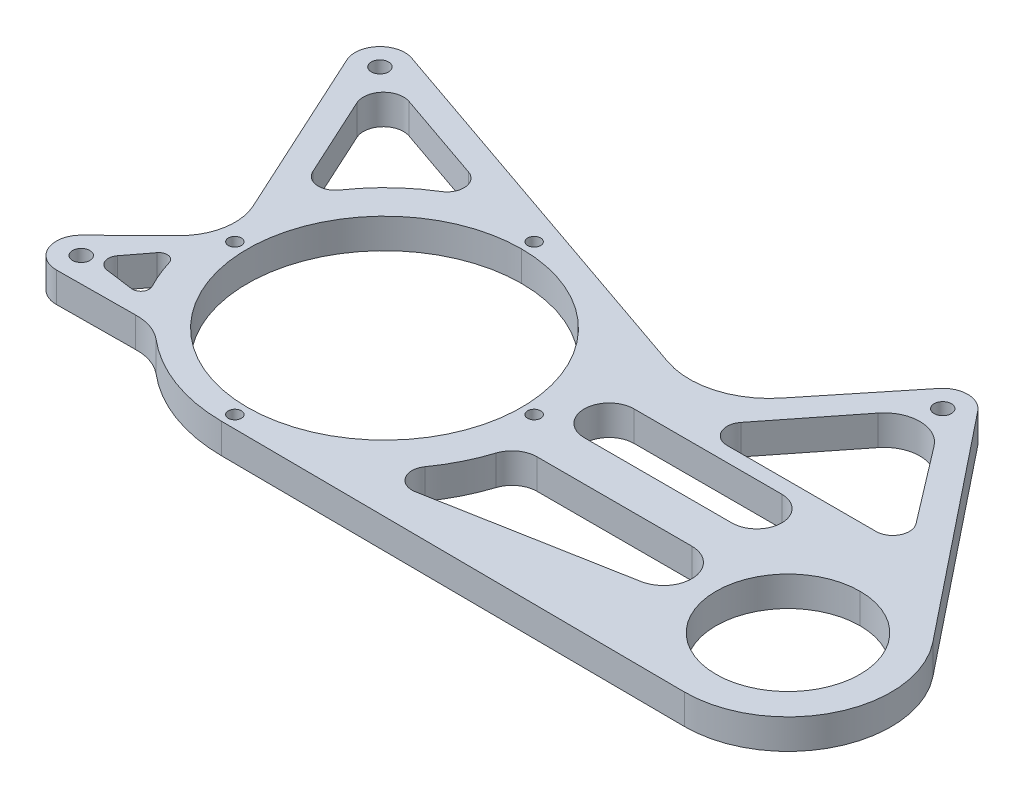
SolidWorks part; units mm, degrees
material "7075-T6 (SN)"
ref_plane "X-Y Datum" through (0, 0, 0) normal (0, 0, 1) x (1, 0, 0)
ref_plane "X-Z Datum" through (0, 0, 0) normal (0, 1, 0) x (1, 0, 0)
ref_plane "Y-Z Datum" through (0, 0, 0) normal (1, 0, 0) x (0, 0, -1)
sketch "Sketch1" plane through (0, 0, 0) normal (0, 1, 0) x (1, 0, 0)
  line L1 (0, 0) -> (54.61, -127) construction
  line L2 (-123.19, -103.3015) -> (54.61, -127) construction
  line L3 (-228.6, -146.8882) -> (-228.6, 0) construction
  line L4 (-116.84, 0) -> (0, 0) construction
  line L5 (-228.6, 0) -> (-116.84, 0) construction
  line L10 (-228.6, 0) -> (-123.19, -103.3015) construction
  line L11 (-123.19, -103.3015) -> (10.0337, -23.3342) construction
  line L15 (-207.3527, -8.7739) -> (-58.0195, -60.2909)
  line L16 (-123.5924, -165.2127) -> (54.3541, -166.3692)
  line L17 (17.4773, -17.3912) -> (85.3768, -102.4358)
  line L18 (2.625, -17.3478) -> (-24.2401, -50.596)
  line L21 (-219.114, -21.7551) -> (-188.6781, -87.992)
  line L23 (-228.6, -146.8882) -> (-123.19, -103.3015) construction
  line L26 (-205.0543, -146.7071) -> (-175.1551, -146.4772)
  line L27 (-211.8024, -130.3874) -> (-193.0929, -112.0085)
  circle A0 centre (-210.459, -17.7782) radius 9.525 construction
  circle A2 centre (10.0337, -23.3342) radius 9.525 construction
  circle A3 centre (-210.459, -17.7782) radius 3.3 construction
  circle A4 centre (-205.1275, -137.1824) radius 3.3 construction
  circle A5 centre (-123.19, -103.3015) radius 52.3875
  circle A6 centre (54.61, -127) radius 27.5
  circle A7 centre (0, 0) radius 12.7 construction
  circle A8 centre (-228.6, -146.8882) radius 12.7 construction
  circle A9 centre (-228.6, 0) radius 12.7 construction
  circle A10 centre (10.0337, -23.3342) radius 3.3 construction
  circle A11 centre (-123.19, -160.4515) radius 2.5 construction
  circle A14 centre (-123.19, -103.3015) radius 61.9125 construction
  circle A15 centre (-123.19, -103.3015) radius 57.15 construction
  circle A17 centre (-205.1275, -137.1824) radius 9.525 construction
  circle A18 centre (54.61, -127) radius 39.37 construction
  circle A19 centre (-48.0406, -31.3647) radius 30.5991 construction
  arc A20 (-24.2401, -50.596) -> (-58.0195, -60.2909) centre (-48.0406, -31.3647) cw
  arc A24 (54.3541, -166.3692) -> (85.3768, -102.4358) centre (54.61, -127) ccw
  arc A25 (2.625, -17.3478) -> (17.4773, -17.3912) centre (10.0337, -23.3342) cw
  arc A30 (-219.114, -21.7551) -> (-207.3527, -8.7739) centre (-210.459, -17.7782) cw
  arc A31 (-163.2991, -150.4652) -> (-123.5924, -165.2127) centre (-123.19, -103.3015) ccw
  circle A35 centre (-207.9749, -96.8588) radius 21.2365 construction
  arc A40 (-193.0929, -112.0085) -> (-188.6781, -87.992) centre (-207.9749, -96.8588) ccw
  arc A41 (-175.1551, -146.4772) -> (-163.2991, -150.4652) centre (-174.5689, -164.3518) cw
  arc A42 (-211.8024, -130.3874) -> (-205.0543, -146.7071) centre (-205.1275, -137.1824) ccw
  dimension "D1" = 146.8882
  dimension "D2" = 105.41
  dimension "D8" = 25.4
  dimension "D9" = 104.775
  dimension "D10" = 55
  dimension "D11" = 19.05
  dimension "D12" = 6.6
  dimension "D23" = 5
  dimension "D14" = 123.825
  dimension "D20" = 31.3647
  dimension "D16" = 78.74
  dimension "D25" = 9.2948
  dimension "D21" = 20.9
  dimension "D26" = 11.856
  dimension "D22" = 17.8843
  dimension "D6" = 25.4
  dimension "D3" = 111.76
  dimension "D4" = 228.6
  dimension "D5" = 127
  dimension "D7" = 283.21
  dimension "D13" = 25.4
  dimension "D15" = 103.3015
  dimension "D17" = 25.4
  dimension "D18" = 48.0406
  dimension "D24" = 57.15
  dimension "D28" = 84.7849
extrude "Boss-Extrude1" add sketch "Sketch1" along normal blind 11.43
hole_wizard "M6 Clearance Hole1" positions "Sketch2" profile "Sketch3" hole size "M6" standard "ANSI Metric" end condition through all
sketch "Sketch2" plane through (0, 0, 0) normal (0, -1, 0) x (-1, 0, 0)
  point P0 (-10.0337, -23.3342)
  point P3 (210.459, -17.7782)
  point P6 (205.1275, -137.1824)
sketch "Sketch3" plane through (10.0337, 0, 23.3342) normal (1, 0, 0) x (0, 0, -1)
  line L0 (0, 0) -> (0, 11.43)
  line L1 (0, 11.43) -> (3.3, 11.43)
  line L2 (3.3, 11.43) -> (3.3, 0)
  line L5 (3.3, 0) -> (0, 0)
  line L11 (0, -6.35) -> (0, 107.95) construction
  dimension "Thru Hole Dia." = 6.6
  dimension "Thru Hole Depth" = 11.43
hole_wizard "Ø5.0mm Dowel Hole1" positions "Sketch4" profile "Sketch5" hole size "Ø5.0" standard "ANSI Metric" end condition through all
sketch "Sketch4" plane through (0, 0, 0) normal (0, -1, 0) x (-1, 0, 0)
  point P0 (123.19, -160.4515)
sketch "Sketch5" plane through (-123.19, 0, 160.4515) normal (1, 0, 0) x (0, 0, -1)
  line L0 (0, 0) -> (0, 11.43)
  line L1 (0, 11.43) -> (2.5, 11.43)
  line L2 (2.5, 11.43) -> (2.5, 0)
  line L5 (2.5, 0) -> (0, 0)
  line L11 (0, -6.35) -> (0, 107.95) construction
  dimension "Thru Hole Dia." = 5
  dimension "Thru Hole Depth" = 11.43
pattern_circular "CirPattern1" count 4 over 360 about axis through (-123.19, 0, 103.3015) along (0, 1, 0) of "Ø5.0mm Dowel Hole1"
ref_point "Point1"
ref_point "Point2"
ref_plane "Plane1" through (-123.19, 0, 0) normal (1, 0, 0) x (0, 0, -1)
ref_plane "Plane2" through (54.61, 0, 0) normal (1, 0, 0) x (0, 0, -1)
split line "Split Line1"
split line "Split Line2"
sketch "Sketch6" plane through (0, 0, 0) normal (0, -1, 0) x (1, 0, 0)
  line L0 (-23.9443, 66.3904) -> (-0.8296, 37.1)
  line L1 (20.678, 37.2701) -> (42.9808, 66.4698)
  line L2 (-202.9755, 34.0642) -> (-188.6561, 65.2271)
  line L3 (-193.5158, 23.6232) -> (-158.7814, 35.6059)
  line L5 (-18.9595, 76.6742) -> (37.9345, 76.6742)
  line L8 (-219.114, 21.7551) -> (-188.6781, 87.992) construction
  line L9 (17.4773, 17.3912) -> (85.3768, 102.4358) construction
  line L10 (2.625, 17.3478) -> (-24.2401, 50.596) construction
  line L11 (-207.3527, 8.7739) -> (-58.0195, 60.2909) construction
  line L19 (-205.1275, 137.1824) -> (-183.925, 128.4152) construction
  line L21 (-195.3828, 137.0841) -> (-184.6024, 138.5481)
  line L22 (-198.1591, 130.3699) -> (-191.5609, 121.7198)
  circle A0 centre (10.0337, 23.3342) radius 3.3 construction
  circle A1 centre (10.0337, 23.3342) radius 3.3 construction
  arc A2 (54.61, 99.5) -> (54.61, 154.5) centre (54.61, 127) ccw construction
  circle A3 centre (-18.9595, 70.3242) radius 6.35 construction
  circle A4 centre (37.9345, 70.3242) radius 6.35 construction
  circle A5 centre (9.8582, 45.5343) radius 13.6149 construction
  arc A6 (-0.8296, 37.1) -> (20.678, 37.2701) centre (9.8582, 45.5343) ccw
  arc A8 (42.9808, 66.4698) -> (37.9345, 76.6742) centre (37.9345, 70.3242) ccw
  arc A9 (-23.9443, 66.3904) -> (-18.9595, 76.6742) centre (-18.9595, 70.3242) cw
  circle A10 centre (-182.7707, 62.5228) radius 6.477 construction
  circle A11 centre (-160.8937, 41.7288) radius 6.477 construction
  circle A14 centre (-196.0142, 30.8655) radius 7.6611 construction
  arc A15 (-202.9755, 34.0642) -> (-193.5158, 23.6232) centre (-196.0142, 30.8655) ccw
  circle A24 centre (-184.1734, 135.3894) radius 3.1877 construction
  arc A25 (-158.7814, 35.6059) -> (-157.5113, 47.2525) centre (-160.8937, 41.7288) ccw
  circle A26 centre (-123.19, 103.3015) radius 65.7225
  circle A27 centre (-123.19, 103.3015) radius 65.7225 construction
  arc A28 (-157.5113, 47.2525) -> (-177.4258, 66.181) centre (-123.19, 103.3015) cw
  arc A29 (-188.6561, 65.2271) -> (-177.4258, 66.181) centre (-182.7707, 62.5228) cw
  circle A38 centre (-189.0263, 123.6532) radius 3.1877 construction
  circle A39 centre (-194.8171, 132.9191) radius 4.2032 construction
  arc A40 (-185.9808, 122.7117) -> (-181.3524, 133.9051) centre (-123.19, 103.3015) cw
  arc A41 (-198.1591, 130.3699) -> (-195.3828, 137.0841) centre (-194.8171, 132.9191) cw
  arc A42 (-184.6024, 138.5481) -> (-181.3524, 133.9051) centre (-184.1734, 135.3894) cw
  arc A43 (-191.5609, 121.7198) -> (-185.9808, 122.7117) centre (-189.0263, 123.6532) ccw
  dimension "D3" = 12.7
  dimension "D4" = 22.2001
  dimension "D5" = 12.954
  dimension "D9" = 6.3754
  dimension "D10" = 6.35
  dimension "D12" = 8.4065
  dimension "D1" = 358.769
  dimension "D2" = 0.66
  dimension "D6" = 46.99
  dimension "D7" = 14.4448
  dimension "D8" = 3.81
  dimension "D11" = 11.1571
extrude "Cut-Extrude1" cut sketch "Sketch6" against normal through all
sketch "Sketch7" plane through (0, 0, 0) normal (0, -1, 0) x (1, 0, 0)
  line L0 (-48.8157, 101.3965) -> (7.5723, 101.3965)
  line L1 (-48.8157, 82.3465) -> (7.5723, 82.3465)
  line L4 (-63.1855, 151.5242) -> (9.5279, 138.1299)
  line L6 (-51.5252, 116.7185) -> (7.5723, 116.7185)
  line L7 (-123.19, 103.3015) -> (54.61, 127) construction
  circle A0 centre (-48.8157, 91.8715) radius 9.525 construction
  circle A3 centre (7.5723, 91.8715) radius 9.525 construction
  arc A4 (-48.8157, 82.3465) -> (-48.8157, 101.3965) centre (-48.8157, 91.8715) cw
  arc A5 (7.5723, 82.3465) -> (7.5723, 101.3965) centre (7.5723, 91.8715) ccw
  circle A12 centre (-51.5252, 126.2435) radius 9.525 construction
  circle A14 centre (-64.3589, 145.1544) radius 6.477 construction
  arc A15 (-60.5967, 123.3394) -> (-69.6366, 141.3998) centre (-123.19, 103.3015) ccw
  arc A16 (-69.6366, 141.3998) -> (-63.1855, 151.5242) centre (-64.3589, 145.1544) cw
  arc A17 (-60.5967, 123.3394) -> (-51.5252, 116.7185) centre (-51.5252, 126.2435) ccw
  circle A19 centre (7.5723, 127.5135) radius 10.795 construction
  arc A20 (9.5279, 138.1299) -> (7.5723, 116.7185) centre (7.5723, 127.5135) cw
  circle A28 centre (-123.19, 103.3015) radius 65.7225
  circle A29 centre (-123.19, 103.3015) radius 65.7225 construction
  dimension "D1" = 19.05
  dimension "D2" = 11.43
  dimension "D5" = 12.954
  dimension "D8" = 35.642
  dimension "D3" = 21.59
  dimension "D4" = 56.388
  dimension "D7" = 33.7133
  dimension "D6" = 3.81
extrude "Cut-Extrude2" cut sketch "Sketch7" against normal through all
sketch "Sketch8" [suppressed] plane through (0, 0, 0) normal (0, -1, 0) x (1, 0, 0)
  line L0 (21.6652, 38.5626) -> (42.9808, 66.4698) construction
  line L1 (-10.1828, 67.6907) -> (2.0865, 40.7709) construction
  line L2 (37.9345, 76.6742) -> (-4.4047, 76.6742) construction
  line L3 (21.6652, 38.5626) -> (42.9808, 66.4698)
  line L4 (-10.1828, 67.6907) -> (2.0865, 40.7709)
  line L5 (37.9345, 76.6742) -> (-4.4047, 76.6742)
  arc A0 (42.9808, 66.4698) -> (37.9345, 76.6742) centre (37.9345, 70.3242) ccw construction
  arc A1 (2.0865, 40.7709) -> (21.6652, 38.5626) centre (12.5377, 45.5343) ccw construction
  arc A2 (-4.4047, 76.6742) -> (-10.1828, 67.6907) centre (-4.4047, 70.3242) ccw construction
  arc A3 (42.9808, 66.4698) -> (37.9345, 76.6742) centre (37.9345, 70.3242) ccw
  arc A4 (2.0865, 40.7709) -> (21.6652, 38.5626) centre (12.5377, 45.5343) ccw
  arc A5 (-4.4047, 76.6742) -> (-10.1828, 67.6907) centre (-4.4047, 70.3242) ccw
extrude "Boss-Extrude3" [suppressed] add sketch "Sketch8" against normal blind 11.43
